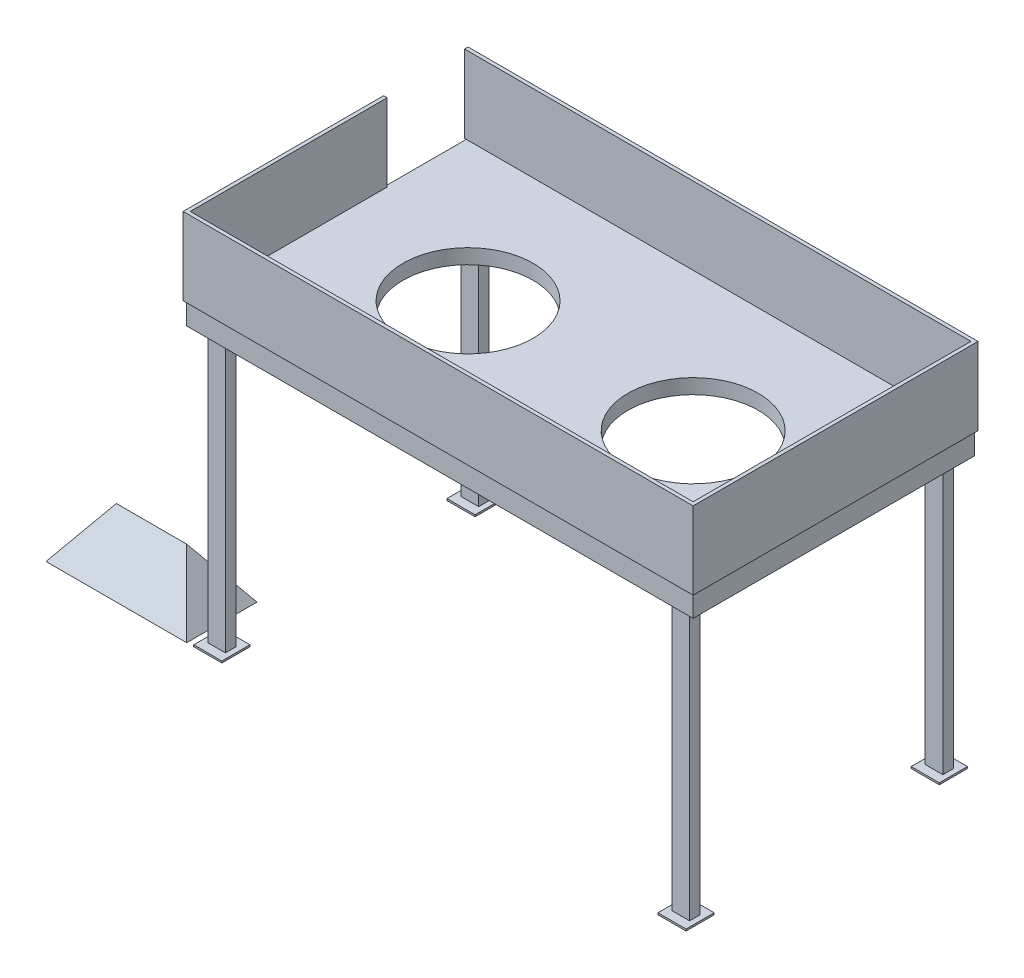
SolidWorks part; units mm, degrees
ref_plane "Front Plane" through (0, 0, 0) normal (0, 0, 1) x (1, 0, 0)
ref_plane "Top Plane" through (0, 0, 0) normal (0, 1, 0) x (1, 0, 0)
ref_plane "Right Plane" through (0, 0, 0) normal (1, 0, 0) x (0, 0, -1)
other "Configuration Table"
sketch "Sketch1" plane through (0, 0, 0) normal (0, 1, 0) x (1, 0, 0)
  line L1 (-3500, -2000) -> (-3100, -2000)
  line L2 (-3500, -2000) -> (-3500, -1600)
  line L3 (-3500, -1600) -> (-3100, -1600)
  line L4 (-3100, -2000) -> (-3100, -1600)
extrude "Boss-Extrude1" add sketch "Sketch1" along normal blind 25
sketch "Sketch2" plane through (0, 0, 0) normal (0, 1, 0) x (1, 0, 0)
  line L1 (-3500, 1600) -> (-3100, 1600)
  line L2 (-3500, 1600) -> (-3500, 2000)
  line L3 (-3500, 2000) -> (-3100, 2000)
  line L4 (-3100, 1600) -> (-3100, 2000)
extrude "Boss-Extrude2" add sketch "Sketch2" along normal blind 25
sketch "Sketch3" plane through (0, 0, 0) normal (0, 1, 0) x (1, 0, 0)
  line L1 (3100, -2000) -> (3500, -2000)
  line L2 (3100, -2000) -> (3100, -1600)
  line L3 (3100, -1600) -> (3500, -1600)
  line L4 (3500, -2000) -> (3500, -1600)
extrude "Boss-Extrude3" add sketch "Sketch3" along normal blind 25
sketch "Sketch4" plane through (0, 0, 0) normal (0, 1, 0) x (1, 0, 0)
  line L1 (3100, 1600) -> (3500, 1600)
  line L2 (3100, 1600) -> (3100, 2000)
  line L3 (3100, 2000) -> (3500, 2000)
  line L4 (3500, 1600) -> (3500, 2000)
extrude "Boss-Extrude4" add sketch "Sketch4" along normal blind 25
sketch "Sketch5" plane through (0, 0, 0) normal (0, 1, 0) x (1, 0, 0)
  line L1 (-3425, -1875) -> (-3175, -1875)
  line L2 (-3425, -1875) -> (-3425, -1725)
  line L3 (-3425, -1725) -> (-3175, -1725)
  line L4 (-3175, -1875) -> (-3175, -1725)
extrude "Boss-Extrude5" add sketch "Sketch5" along normal blind 4175 from offset 25
sketch "Sketch6" plane through (0, 0, 0) normal (0, 1, 0) x (1, 0, 0)
  line L1 (-3425, 1725) -> (-3175, 1725)
  line L2 (-3425, 1725) -> (-3425, 1875)
  line L3 (-3425, 1875) -> (-3175, 1875)
  line L4 (-3175, 1725) -> (-3175, 1875)
extrude "Boss-Extrude6" add sketch "Sketch6" along normal blind 4175 from offset 25
sketch "Sketch7" plane through (0, 0, 0) normal (0, 1, 0) x (1, 0, 0)
  line L1 (3175, -1875) -> (3425, -1875)
  line L2 (3175, -1875) -> (3175, -1725)
  line L3 (3175, -1725) -> (3425, -1725)
  line L4 (3425, -1875) -> (3425, -1725)
extrude "Boss-Extrude7" add sketch "Sketch7" along normal blind 4175 from offset 25
sketch "Sketch8" plane through (0, 0, 0) normal (0, 1, 0) x (1, 0, 0)
  line L1 (3175, 1725) -> (3425, 1725)
  line L2 (3175, 1725) -> (3175, 1875)
  line L3 (3175, 1875) -> (3425, 1875)
  line L4 (3425, 1725) -> (3425, 1875)
extrude "Boss-Extrude8" add sketch "Sketch8" along normal blind 4175 from offset 25
sketch "Sketch9" plane through (0, 0, 0) normal (0, 1, 0) x (1, 0, 0)
  line L1 (-3600, -2000) -> (3600, -2000)
  line L2 (-3600, -2000) -> (-3600, -1860)
  line L3 (-3600, -1860) -> (3600, -1860)
  line L4 (3600, -2000) -> (3600, -1860)
extrude "Boss-Extrude9" add sketch "Sketch9" along normal blind 300 from offset 3900
sketch "Sketch10" plane through (0, 0, 0) normal (0, 1, 0) x (1, 0, 0)
  line L1 (-3600, 1860) -> (3600, 1860)
  line L2 (-3600, 1860) -> (-3600, 2000)
  line L3 (-3600, 2000) -> (3600, 2000)
  line L4 (3600, 1860) -> (3600, 2000)
extrude "Boss-Extrude10" add sketch "Sketch10" along normal blind 300 from offset 3900
sketch "Sketch11" plane through (0, 0, 0) normal (0, 1, 0) x (1, 0, 0)
  line L0 (3600, 2000) -> (-3600, 2000) construction
  line L1 (-3600, -2000) -> (-3460, -2000)
  line L2 (-3600, -2000) -> (-3600, 2000)
  line L3 (-3600, 2000) -> (-3460, 2000)
  line L4 (-3460, -2000) -> (-3460, 2000)
extrude "Boss-Extrude11" add sketch "Sketch11" along normal blind 300 from offset 3900
sketch "Sketch12" plane through (0, 0, 0) normal (0, 1, 0) x (1, 0, 0)
  line L0 (-3600, -2000) -> (3600, -2000) construction
  line L1 (3460, -2000) -> (3600, -2000)
  line L2 (3460, -2000) -> (3460, 2000)
  line L3 (3460, 2000) -> (3600, 2000)
  line L4 (3600, -2000) -> (3600, 2000)
extrude "Boss-Extrude12" add sketch "Sketch12" along normal blind 300 from offset 3900
sketch "Sketch13" plane through (0, 0, 0) normal (0, 1, 0) x (1, 0, 0)
  line L1 (-3600, -2000) -> (3600, -2000)
  line L2 (-3600, -2000) -> (-3600, 2000)
  line L3 (-3600, 2000) -> (3600, 2000)
  line L4 (3600, -2000) -> (3600, 2000)
  circle A0 centre (-1600, 0) radius 925
  circle A1 centre (1600, 0) radius 925
extrude "Boss-Extrude13" add sketch "Sketch13" along normal blind 10 from offset 4200
sketch "Sketch14" plane through (0, 0, 0) normal (0, 1, 0) x (1, 0, 0)
  circle A0 centre (-1600, 0) radius 1080
  circle A1 centre (-1600, 0) radius 925
extrude "Boss-Extrude14" add sketch "Sketch14" along normal blind 200 from offset 4000
sketch "Sketch15" plane through (0, 0, 0) normal (0, 1, 0) x (1, 0, 0)
  circle A0 centre (1600, 0) radius 1080
  circle A1 centre (1600, 0) radius 925
extrude "Boss-Extrude15" add sketch "Sketch15" along normal blind 200 from offset 4000
sketch "Sketch16" plane through (0, 0, 0) normal (0, 1, 0) x (1, 0, 0)
  line L1 (-3625, -2025) -> (3625, -2025)
  line L2 (-3625, -2025) -> (-3625, -1975)
  line L3 (-3625, -1975) -> (3625, -1975)
  line L4 (3625, -2025) -> (3625, -1975)
extrude "Boss-Extrude16" add sketch "Sketch16" along normal blind 1100 from offset 4210
sketch "Sketch17" plane through (0, 0, 0) normal (0, 1, 0) x (1, 0, 0)
  line L0 (-3625, -2025) -> (3625, -2025) construction
  line L1 (3575, -2025) -> (3625, -2025)
  line L2 (3575, -2025) -> (3575, 2025)
  line L3 (3575, 2025) -> (3625, 2025)
  line L4 (3625, -2025) -> (3625, 2025)
extrude "Boss-Extrude17" add sketch "Sketch17" along normal blind 1100 from offset 4210
sketch "Sketch18" plane through (0, 0, 0) normal (0, 1, 0) x (1, 0, 0)
  line L1 (-3625, 1975) -> (3625, 1975)
  line L2 (-3625, 1975) -> (-3625, 2025)
  line L3 (-3625, 2025) -> (3625, 2025)
  line L4 (3625, 1975) -> (3625, 2025)
extrude "Boss-Extrude18" add sketch "Sketch18" along normal blind 1100 from offset 4210
sketch "Sketch19" plane through (0, 0, 0) normal (0, 1, 0) x (1, 0, 0)
  line L1 (-3625, -2025) -> (-3575, -2025)
  line L2 (-3625, -2025) -> (-3625, 825)
  line L3 (-3625, 825) -> (-3575, 825)
  line L4 (-3575, -2025) -> (-3575, 825)
extrude "Boss-Extrude19" add sketch "Sketch19" along normal blind 1100 from offset 4210
sketch "Sketch20" plane through (0, 0, 0) normal (0, 1, 0) x (1, 0, 0)
  line L1 (-5600, -2000) -> (-3600, -2000)
  line L2 (-5600, -2000) -> (-5600, -1000)
  line L3 (-5600, -1000) -> (-3600, -1000)
  line L4 (-3600, -2000) -> (-3600, -1000)
extrude "Boss-Extrude20" add sketch "Sketch20" along normal blind 2100 draft 35
